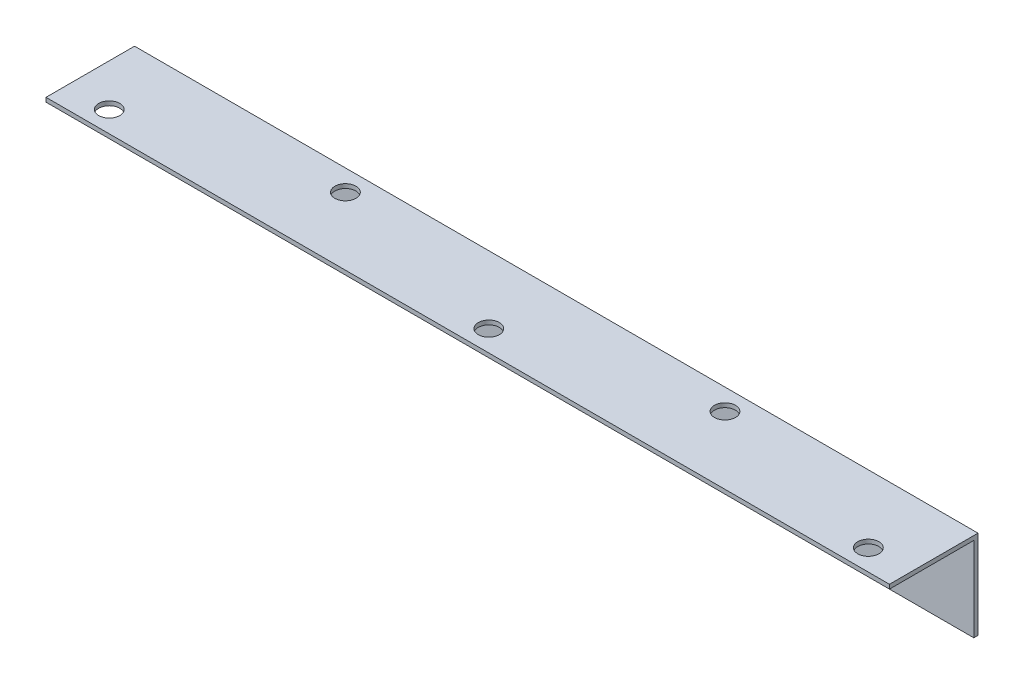
SolidWorks part; units mm, degrees
ref_plane "Front Plane" through (0, 0, 0) normal (0, 0, 1) x (1, 0, 0)
ref_plane "Top Plane" through (0, 0, 0) normal (0, 1, 0) x (1, 0, 0)
ref_plane "Right Plane" through (0, 0, 0) normal (1, 0, 0) x (0, 0, -1)
sketch "Sketch1" plane through (0, 0, 0) normal (0, 0, 1) x (1, 0, 0)
  line L1 (0, 0) -> (-200, 0)
  line L2 (0, 0) -> (0, 20)
  line L3 (0, 20) -> (-200, 20)
  line L4 (-200, 0) -> (-200, 20)
  dimension "D1" = 200
  dimension "D2" = 20
extrude "Boss-Extrude1" add sketch "Sketch1" along normal blind 1
ref_plane "Plane1" through (0, 20, 0) normal (0, 1, 0) x (1, 0, 0)
sketch "Sketch4" plane through (0, 20, 0) normal (0, 1, 0) x (1, 0, 0)
  line L1 (-200, 0) -> (0, 0)
  line L2 (-200, 0) -> (-200, -21)
  line L3 (-200, -21) -> (0, -21)
  line L4 (0, 0) -> (0, -21)
  circle A0 centre (-190, -16) radius 2.5
  circle A1 centre (-145, -5) radius 2.5
  circle A2 centre (-100, -16) radius 2.5
  circle A3 centre (-55, -5) radius 2.5
  circle A4 centre (-10, -16) radius 2.5
  dimension "D3" = 5
  dimension "D4" = 5
  dimension "D5" = 5
  dimension "D6" = 5
  dimension "D7" = 5
  dimension "D1" = 200
  dimension "D2" = 21
  dimension "D8" = 5
  dimension "D9" = 5
  dimension "D10" = 10
  dimension "D11" = 10
  dimension "D12" = 45
  dimension "D13" = 45
  dimension "D14" = 45
extrude "Boss-Extrude2" add sketch "Sketch4" along normal blind 1
sketch "Sketch5" plane through (0, 0, 1) normal (0, 0, 1) x (1, 0, 0)
  line L0 (-200, 20) -> (-200, 0) construction
  circle A0 centre (-140, 9.3725) radius 4
  circle A1 centre (-60, 9.3725) radius 4
  dimension "D1" = 8
  dimension "D2" = 8
  dimension "D3" = 80
  dimension "D4" = 60
extrude "Cut-Extrude1" cut sketch "Sketch5" against normal blind 10
